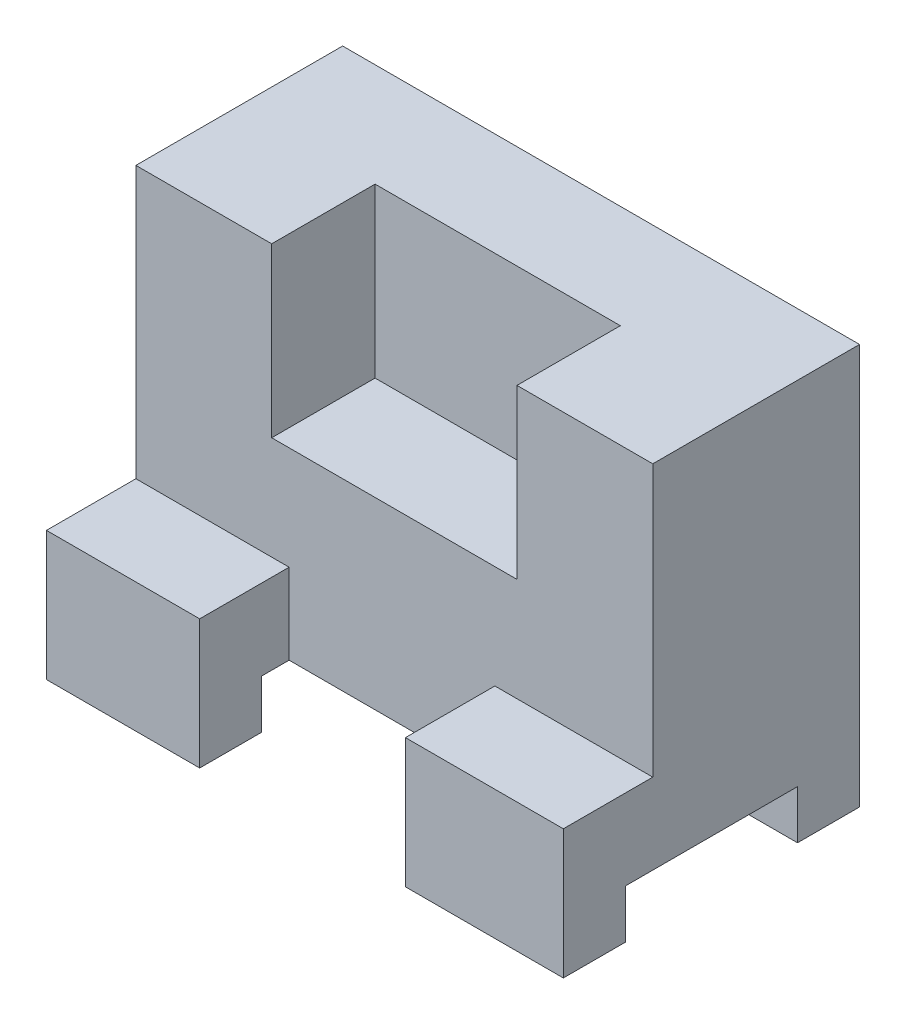
SolidWorks part; units mm, degrees
material "Cast Alloy Steel"
ref_plane "Front Plane" through (0, 0, 0) normal (0, 0, 1) x (1, 0, 0)
ref_plane "Top Plane" through (0, 0, 0) normal (0, 1, 0) x (1, 0, 0)
ref_plane "Right Plane" through (0, 0, 0) normal (1, 0, 0) x (0, 0, -1)
sketch "Sketch1" plane through (0, 0, 0) normal (0, 0, 1) x (1, 0, 0)
  line L1 (-127, -82.55) -> (127, -82.55)
  line L2 (-127, -82.55) -> (-127, 82.55)
  line L3 (-127, 82.55) -> (127, 82.55)
  line L4 (127, -82.55) -> (127, 82.55)
  line L5 (-127, -82.55) -> (127, 82.55) construction
  line L6 (-127, 82.55) -> (127, -82.55) construction
  point P0 (0, 0)
  dimension "D1" = 254
  dimension "D2" = 165.1
extrude "Boss-Extrude1" add sketch "Sketch1" along normal blind 101.6
sketch "Sketch2" plane through (0, 0, 101.6) normal (0, 0, 1) x (1, 0, 0)
  line L0 (0, 0) -> (0, 82.55) construction
  line L1 (127, 82.55) -> (-127, 82.55) construction
  line L2 (-60.2599, 82.55) -> (60.2599, 82.55)
  line L3 (60.2599, 82.55) -> (60.2599, 0)
  line L4 (60.2599, 0) -> (-60.2599, 0)
  line L5 (-60.2599, 82.55) -> (-60.2599, 0)
  dimension "D1" = 120.5198
extrude "Cut-Extrude1" cut sketch "Sketch2" against normal blind 50.8
ref_plane "Plane1" through (0, -82.55, 0) normal (0, -1, 0) x (-1, 0, 0)
sketch "Sketch3" plane through (0, -82.55, 0) normal (0, -1, 0) x (-1, 0, 0)
  line L0 (-127, -101.6) -> (-127, -145.5443)
  line L1 (-127, -145.5443) -> (-49.4064, -145.5436)
  line L2 (127, -145.542) -> (127, -101.6)
  line L3 (127, -101.6) -> (127, 0)
  line L4 (127, 0) -> (-127, 0)
  line L5 (-127, 0) -> (-127, -101.6)
  line L8 (-49.4064, -145.5436) -> (-49.4064, -101.6)
  line L9 (127, -101.6) -> (-127, -101.6) construction
  line L10 (-49.4064, -101.6) -> (51.7028, -101.6)
  line L11 (51.7028, -101.6) -> (51.7028, -145.5427)
  line L12 (51.7028, -145.5427) -> (127, -145.542)
  dimension "D1" = 101.1091
  dimension "D2" = 75.2972
  dimension "D3" = 254
  dimension "D4" = 43.9443
  dimension "D5" = 145.5443
  dimension "D6" = 43.942
extrude "Boss-Extrude2" add sketch "Sketch3" along normal mid plane 63.5
sketch "Sketch4" plane through (127, 0, 0) normal (1, 0, 0) x (0, 0, -1)
  line L1 (0, -114.3) -> (-145.5443, -114.3) construction
  line L2 (-115.0643, -114.3) -> (-115.0643, -90.3755)
  line L3 (-115.0643, -90.3755) -> (-30.48, -90.3755)
  line L4 (-30.48, -90.3755) -> (-30.48, -114.3)
  line L6 (-115.0643, -114.3) -> (-30.48, -114.3)
  dimension "D1" = 84.5843
  dimension "D2" = 23.9245
  dimension "D3" = 30.48
extrude "Cut-Extrude2" cut sketch "Sketch4" against normal through all both and the other way through all
